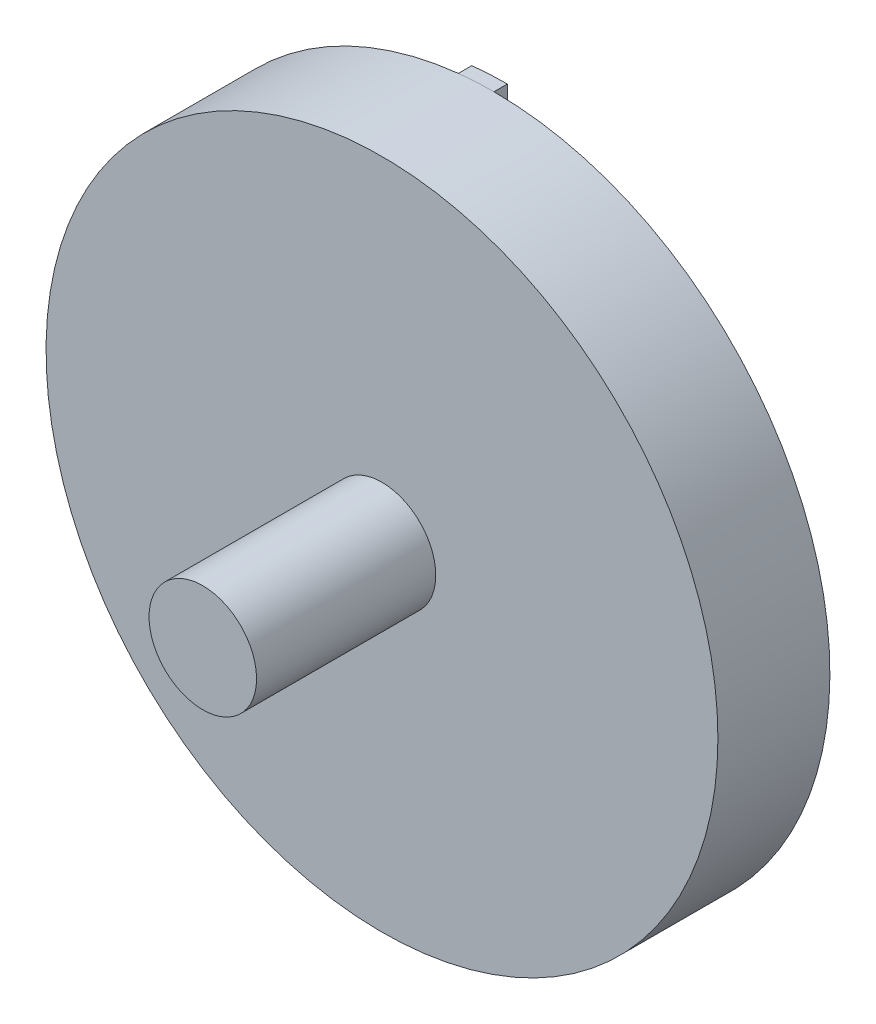
SolidWorks part; units mm, degrees
ref_plane "Front Plane" through (0, 0, 0) normal (0, 0, 1) x (1, 0, 0)
ref_plane "Top Plane" through (0, 0, 0) normal (0, 1, 0) x (1, 0, 0)
ref_plane "Right Plane" through (0, 0, 0) normal (1, 0, 0) x (0, 0, -1)
sketch "Sketch1" plane through (0, 0, 0) normal (0, 0, 1) x (1, 0, 0)
  circle A0 centre (0, 0) radius 75
  dimension "D1" = 150
extrude "Boss-Extrude1" add sketch "Sketch1" along normal blind 25
sketch "Sketch2" plane through (0, 0, 25) normal (0, 0, 1) x (1, 0, 0)
  circle A0 centre (0, 0) radius 12
  dimension "D1" = 24
extrude "Boss-Extrude2" add sketch "Sketch2" along normal blind 40
sketch "Sketch3" plane through (0, 0, 0) normal (0, 0, -1) x (-1, 0, 0)
  line L0 (0, 0) -> (0, 75)
  line L1 (0, 0) -> (7.949, 0)
  line L2 (7.949, 0) -> (7.949, 74.5776)
  circle A0 centre (0, 0) radius 75 construction
  spline S0 degree 2 poles (7.949, 74.5776) (3.9863, 74.9998) (0, 75) knots 0 0 0 1 1 1
  point P9 (4.3482, 74.8738)
extrude "Boss-Extrude3" add sketch "Sketch3" along normal blind 3
